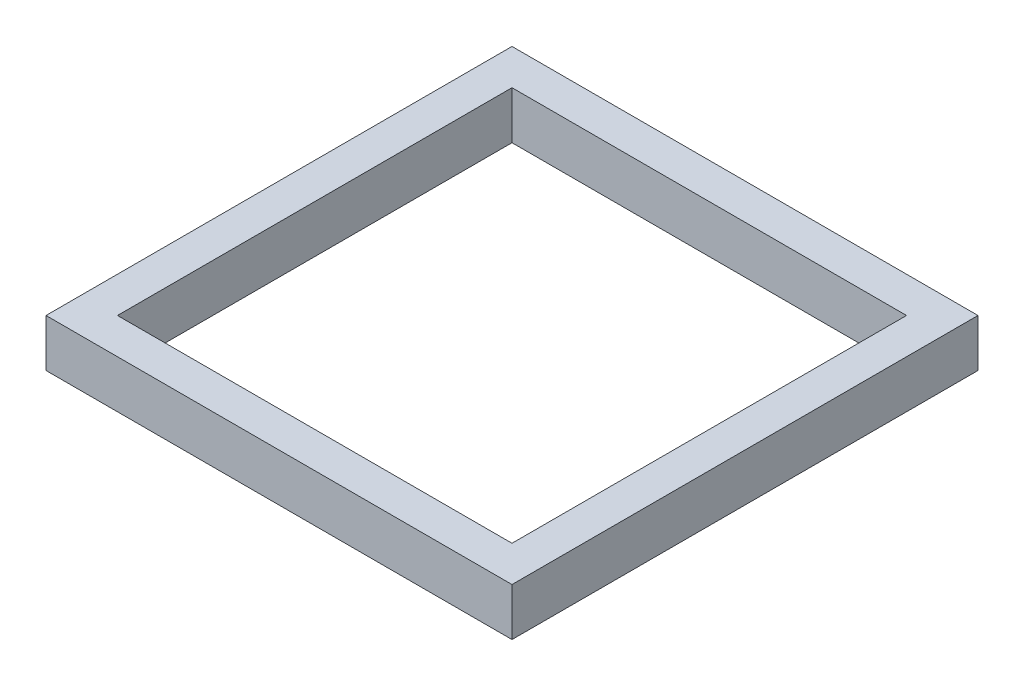
SolidWorks part; units mm, degrees
ref_plane "Front" through (0, 0, 0) normal (0, 0, 1) x (1, 0, 0)
ref_plane "Top" through (0, 0, 0) normal (0, 1, 0) x (1, 0, 0)
ref_plane "Right" through (0, 0, 0) normal (1, 0, 0) x (0, 0, -1)
sketch "Sketch1" plane through (0, 0, 0) normal (0, 1, 0) x (1, 0, 0)
  line L1 (82.76, -82.76) -> (-82.76, -82.76)
  line L2 (82.76, -82.76) -> (82.76, 82.76)
  line L3 (82.76, 82.76) -> (-82.76, 82.76)
  line L4 (-82.76, -82.76) -> (-82.76, 82.76)
  line L5 (82.76, -82.76) -> (-82.76, 82.76) construction
  line L6 (82.76, 82.76) -> (-82.76, -82.76) construction
  line L7 (97.755, -97.755) -> (-97.755, -97.755)
  line L8 (97.755, -97.755) -> (97.755, 97.755)
  line L9 (97.755, 97.755) -> (-97.755, 97.755)
  line L10 (-97.755, -97.755) -> (-97.755, 97.755)
  line L11 (97.755, -97.755) -> (-97.755, 97.755) construction
  line L12 (97.755, 97.755) -> (-97.755, -97.755) construction
  point P0 (0, 0)
  point P6 (0, 0)
  dimension "D1" = 165.52
  dimension "D2" = 195.51
  dimension "D3" = 165.52
  dimension "D4" = 195.51
extrude "Boss-Extrude1" add sketch "Sketch1" along normal blind 20
